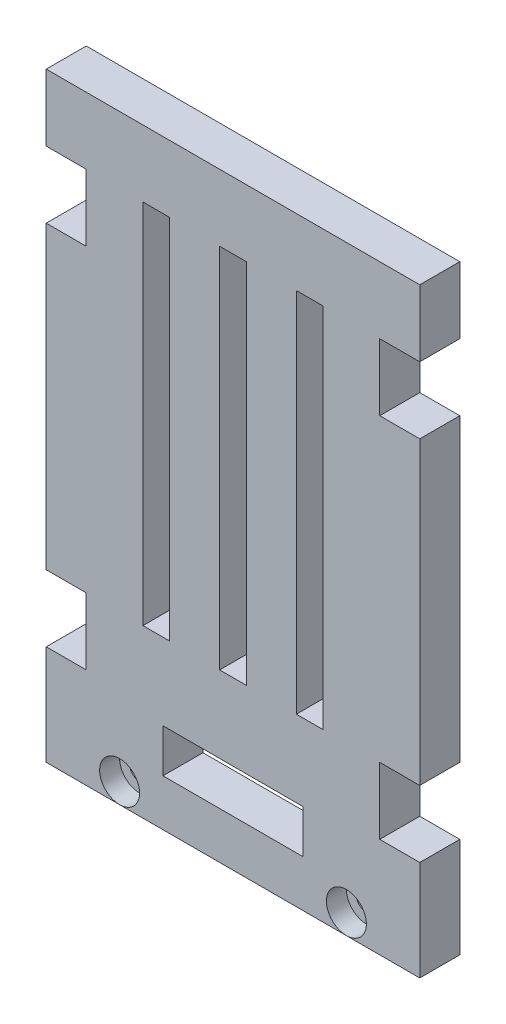
SolidWorks part; units mm, degrees
ref_plane "Plan de face" through (0, 0, 0) normal (0, 0, 1) x (1, 0, 0)
ref_plane "Plan de dessus" through (0, 0, 0) normal (0, 1, 0) x (1, 0, 0)
ref_plane "Plan de droite" through (0, 0, 0) normal (1, 0, 0) x (0, 0, -1)
sketch "Esquisse1" plane through (0, 0, 0) normal (0, 0, 1) x (1, 0, 0)
  line L1 (0, 0) -> (44, 0)
  line L2 (0, 0) -> (0, 90)
  line L3 (0, 90) -> (44, 90)
  line L4 (44, 0) -> (44, 90)
  dimension "D1" = 44
  dimension "D2" = 90
extrude "Boss.-Extru.1" add sketch "Esquisse1" along normal blind 6
sketch "Esquisse2" plane through (0, 0, 6) normal (0, 0, 1) x (1, 0, 0)
  line L0 (44, 90) -> (0, 90) construction
  line L1 (11.5, 13.5) -> (32.5, 13.5)
  line L2 (11.5, 13.5) -> (11.5, 7)
  line L3 (11.5, 7) -> (32.5, 7)
  line L4 (32.5, 13.5) -> (32.5, 7)
  line L5 (0, 90) -> (0, 0) construction
  line L6 (44, 90) -> (0, 90) construction
  line L7 (24, 80) -> (20, 80)
  line L8 (24, 80) -> (24, 25)
  line L9 (24, 25) -> (20, 25)
  line L10 (20, 80) -> (20, 25)
  line L12 (0, 90) -> (0, 0) construction
  line L13 (44, 0) -> (44, 90) construction
  line L15 (31.5, 80) -> (35.5, 80)
  line L16 (31.5, 80) -> (31.5, 25)
  line L17 (31.5, 25) -> (35.5, 25)
  line L18 (35.5, 80) -> (35.5, 25)
  line L19 (12.5, 80) -> (8.5, 80)
  line L20 (12.5, 80) -> (12.5, 25)
  line L21 (12.5, 25) -> (8.5, 25)
  line L22 (8.5, 80) -> (8.5, 25)
  dimension "D1" = 76.5
  dimension "D2" = 6.5
  dimension "D3" = 21
  dimension "D4" = 11.5
  dimension "D5" = 10
  dimension "D6" = 4
  dimension "D7" = 20
  dimension "D8" = 55
  dimension "D9" = 20
  dimension "D10" = 4
  dimension "D11" = 4
  dimension "D12" = 7.5
  dimension "D13" = 7.5
  dimension "D14" = 55
  dimension "D15" = 55
  dimension "D16" = 10
  dimension "D17" = 10
extrude "Enlèv. mat.-Extru.1" cut sketch "Esquisse2" against normal blind 6
sketch "Esquisse4" plane through (0, 0, 6) normal (0, 0, 1) x (1, 0, 0)
  line L0 (0, 90) -> (0, 0) construction
  line L1 (0, 90) -> (-6, 90)
  line L2 (0, 90) -> (0, 80)
  line L3 (0, 80) -> (-6, 80)
  line L4 (-6, 90) -> (-6, 80)
  line L5 (0, 70) -> (-6, 70)
  line L6 (0, 70) -> (0, 25)
  line L7 (0, 25) -> (-6, 25)
  line L8 (-6, 70) -> (-6, 25)
  line L9 (44, 0) -> (44, 90) construction
  line L10 (0, 0) -> (-6, 0)
  line L11 (0, 0) -> (0, 15)
  line L12 (0, 15) -> (-6, 15)
  line L13 (-6, 0) -> (-6, 15)
  line L14 (44, 0) -> (50, 0)
  line L15 (44, 0) -> (44, 15)
  line L16 (44, 15) -> (50, 15)
  line L17 (50, 0) -> (50, 15)
  line L18 (44, 25) -> (50, 25)
  line L19 (44, 25) -> (44, 70)
  line L20 (44, 70) -> (50, 70)
  line L21 (50, 25) -> (50, 70)
  line L23 (44, 90) -> (50, 90)
  line L24 (44, 90) -> (44, 80)
  line L25 (44, 80) -> (50, 80)
  line L26 (50, 90) -> (50, 80)
  dimension "D1" = 6
  dimension "D2" = 6
  dimension "D3" = 6
  dimension "D4" = 6
  dimension "D5" = 6
  dimension "D6" = 6
  dimension "D7" = 10
  dimension "D8" = 10
  dimension "D9" = 45
  dimension "D10" = 10
  dimension "D11" = 10
  dimension "D12" = 45
  dimension "D13" = 10
  dimension "D14" = 10
extrude "Boss.-Extru.2" add sketch "Esquisse4" against normal blind 6
sketch "Esquisse6" plane through (0, 0, 6) normal (0, 0, 1) x (1, 0, 0)
  line L0 (-6, 0) -> (50, 0) construction
  line L2 (-6, 15) -> (-6, 0) construction
  line L3 (50, 0) -> (50, 15) construction
  circle A0 centre (5, 3) radius 1.5
  circle A1 centre (39, 3) radius 1.5
  dimension "D1" = 3
  dimension "D2" = 3
  dimension "D3" = 3
  dimension "D4" = 3
  dimension "D6" = 11
  dimension "D5" = 11
extrude "Enlèv. mat.-Extru.3" cut sketch "Esquisse6" against normal blind 6
sketch "Esquisse8" plane through (0, 0, 6) normal (0, 0, 1) x (1, 0, 0)
  circle A0 centre (5, 3) radius 2.995
  circle A1 centre (39, 3) radius 2.995
  dimension "D1" = 5.99
  dimension "D2" = 5.99
extrude "Enlèv. mat.-Extru.4" cut sketch "Esquisse8" against normal blind 3
